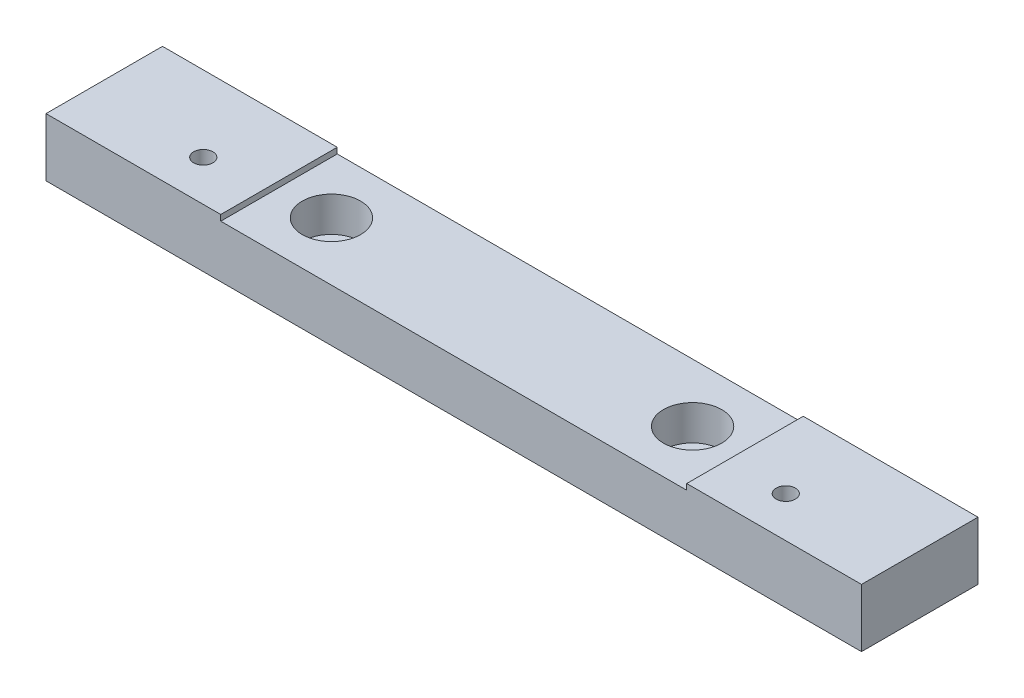
SolidWorks part; units mm, degrees
ref_plane "Front Plane" through (0, 0, 0) normal (0, 0, 1) x (1, 0, 0)
ref_plane "Top Plane" through (0, 0, 0) normal (0, 1, 0) x (1, 0, 0)
ref_plane "Right Plane" through (0, 0, 0) normal (1, 0, 0) x (0, 0, -1)
sketch "Sketch1" plane through (0, 0, 0) normal (0, 1, 0) x (1, 0, 0)
  line L1 (-70, 10) -> (70, 10)
  line L2 (-70, 10) -> (-70, -10)
  line L3 (-70, -10) -> (70, -10)
  line L4 (70, 10) -> (70, -10)
extrude "Boss-Extrude1" add sketch "Sketch1" along normal blind 10
sketch "Sketch2" plane through (0, 10, 0) normal (0, 1, 0) x (1, 0, 0)
  line L0 (70, 10) -> (-70, 10) construction
  line L1 (-40, 10) -> (40, 10)
  line L2 (-40, 10) -> (-40, -10)
  line L3 (-40, -10) -> (40, -10)
  line L4 (40, 10) -> (40, -10)
  line L5 (-70, -10) -> (70, -10) construction
  point P8 (-78.0136, -112.2105)
  point P9 (0, -10)
extrude "Cut-Extrude1" cut sketch "Sketch2" against normal blind 1
sketch "Sketch3" plane through (0, 9, 0) normal (0, 1, 0) x (1, 0, 0)
  circle A0 centre (31, 0) radius 2.75
  circle A1 centre (-31, 0) radius 2.75
extrude "Cut-Extrude2" cut sketch "Sketch3" against normal blind 9
sketch "Sketch4" plane through (0, 9, 0) normal (0, 1, 0) x (1, 0, 0)
  circle A0 centre (31, 0) radius 5
  circle A1 centre (-31, 0) radius 5
extrude "Cut-Extrude3" cut sketch "Sketch4" against normal blind 6
sketch "Sketch5" plane through (0, 10, 0) normal (0, 1, 0) x (1, 0, 0)
  circle A0 centre (-50, -3) radius 1.65
  circle A1 centre (50, -3) radius 1.65
extrude "Cut-Extrude4" cut sketch "Sketch5" against normal blind 10
